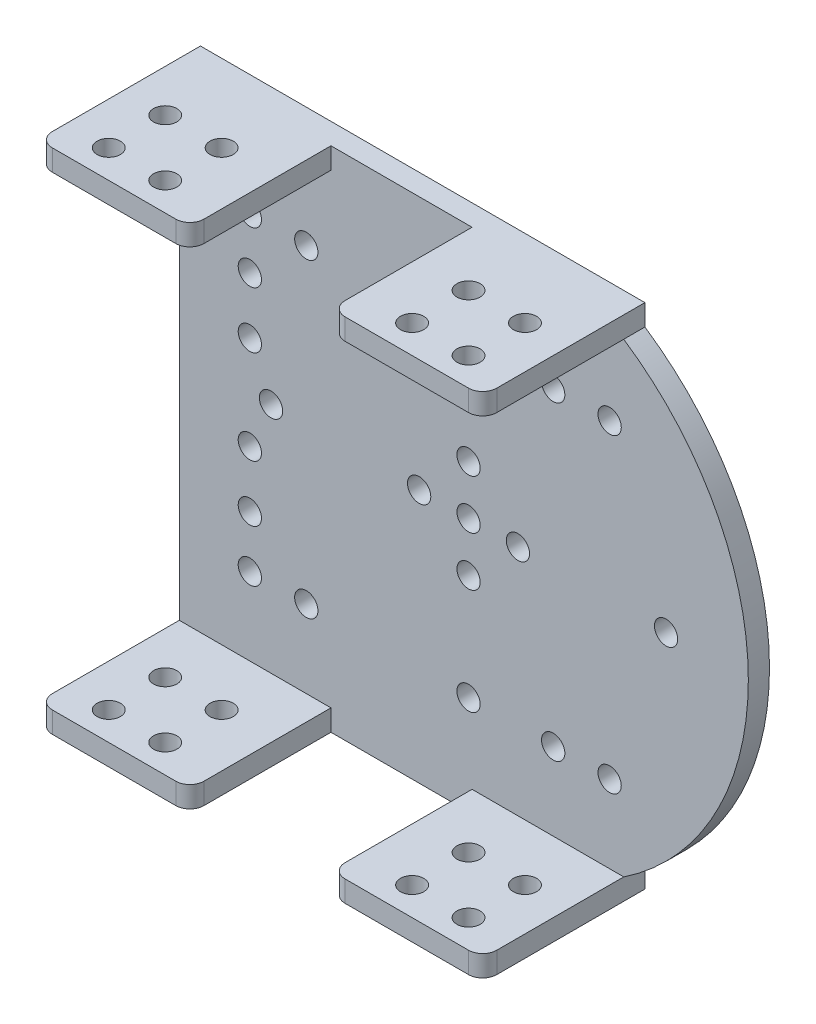
SolidWorks part; units mm, degrees
ref_plane "前视基准面" through (0, 0, 0) normal (0, 0, 1) x (1, 0, 0)
ref_plane "上视基准面" through (0, 0, 0) normal (0, 1, 0) x (1, 0, 0)
ref_plane "右视基准面" through (0, 0, 0) normal (1, 0, 0) x (0, 0, -1)
sketch "草图4" plane through (0, 0, 0) normal (0, 0, 1) x (1, 0, 0)
  line L0 (0, 0) -> (75, 0)
  line L1 (75, 0) -> (75, 72)
  line L2 (75, 72) -> (0, 72)
  line L3 (12, 58) -> (22, 58)
  line L4 (0, 69) -> (75, 69)
  line L5 (0, 3) -> (75, 3)
  line L6 (12, 3) -> (12, 0)
  line L7 (12, 69) -> (12, 3)
  line L8 (22, 72) -> (22, 58)
  line L9 (75, 58) -> (73, 58)
  line L10 (12, 36) -> (39.498, 36)
  line L11 (24, 3) -> (24, 0)
  line L14 (46, 3) -> (46, 0)
  line L15 (58, 3) -> (58, 0)
  line L16 (12, 69) -> (12, 72)
  line L17 (24, 69) -> (24, 72)
  line L18 (46, 69) -> (46, 72)
  line L19 (58, 69) -> (58, 72)
  circle A0 centre (22, 58) radius 1.65
  circle A1 centre (53, 36) radius 1.65
  circle A2 centre (30, 58) radius 1.65
  circle A3 centre (73, 58) radius 1.65
  circle A4 centre (65, 58) radius 1.65
  circle A5 centre (22, 50.65) radius 1.65
  circle A6 centre (53, 58) radius 1.65
  circle A7 centre (22, 42.65) radius 1.65
  circle A8 centre (73, 14) radius 1.65
  circle A9 centre (65, 14) radius 1.65
  circle A10 centre (22, 14) radius 1.65
  circle A11 centre (30, 14) radius 1.65
  circle A12 centre (22, 29.35) radius 1.65
  circle A13 centre (53, 14) radius 1.65
  circle A14 centre (22, 21.35) radius 1.65
  arc A19 (75, 69) -> (75, 3) centre (53, 36) cw
  circle A20 centre (53, 43) radius 1.65
  circle A21 centre (46, 36) radius 1.65
  circle A22 centre (81, 36) radius 1.65
  circle A30 centre (60, 36) radius 1.65
  circle A31 centre (53, 8) radius 1.65
  circle A32 centre (25, 36) radius 1.65
  circle A35 centre (53, 36) radius 11
  circle A36 centre (53, 29) radius 1.65
  dimension "D3" = 72
  dimension "D1" = 11
extrude "凸台-拉伸1" add sketch "草图4" along normal blind 3
sketch "草图5" plane through (0, 0, 3) normal (0, 0, 1) x (1, 0, 0)
  line L0 (12, 72) -> (75, 72)
  line L1 (12, 72) -> (12, 69)
  line L2 (75, 72) -> (75, 69)
  line L3 (12, 69) -> (75, 69)
  line L4 (12, 0) -> (75, 0)
  line L5 (12, 0) -> (12, 3)
  line L6 (75, 0) -> (75, 3)
  line L7 (12, 3) -> (75, 3)
extrude "凸台-拉伸2" add sketch "草图5" along normal blind 20
sketch "草图6" plane through (0, 72, 0) normal (0, 1, 0) x (1, 0, 0)
  line L0 (12, -23) -> (75, -23)
  line L1 (12, -23) -> (12, -3)
  line L2 (75, -23) -> (75, -3)
  line L3 (43.5, -3) -> (53.5, -3)
  line L4 (43.5, -3) -> (43.5, -23)
  line L5 (12, -3) -> (12, -23)
  line L6 (43.5, -3) -> (43.5, -23)
  line L7 (12, -23) -> (20, -23)
  line L8 (53.5, -3) -> (53.5, -23)
  line L9 (43.5, -23) -> (53.5, -23)
  line L10 (43.5, -3) -> (33.5, -3)
  line L11 (43.5, -3) -> (43.5, -23)
  line L12 (33.5, -3) -> (33.5, -23)
  line L13 (43.5, -23) -> (33.5, -23)
  circle A0 centre (18, -11) radius 1.65
  circle A1 centre (18, -19) radius 1.65
  circle A2 centre (26, -19) radius 1.65
  circle A3 centre (26, -11) radius 1.65
  circle A4 centre (61, -19) radius 1.65
  circle A5 centre (69, -19) radius 1.65
  circle A6 centre (69, -11) radius 1.65
  circle A7 centre (61, -11) radius 1.65
extrude "切除-拉伸1" cut sketch "草图6" against normal blind 100 contours A0 | A1 | A2 | A3 | A7 | A4 | A5 | A6 | L13 L4 L10 L12 | L4 L6 L9 L8 L3
fillet "圆角2" radius 2 8 edges at (12, 70.5, 23) (75, 1.5, 23) (53.5, 1.5, 23) (12, 1.5, 23) (33.5, 1.5, 23) (33.5, 70.5, 23) (53.5, 70.5, 23) (75, 70.5, 23)
